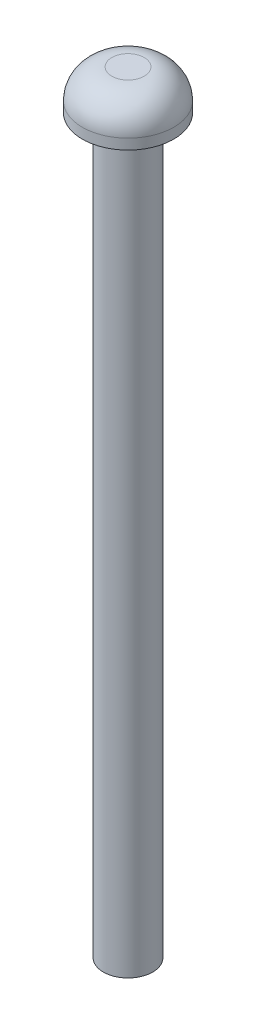
SolidWorks part; units mm, degrees
ref_plane "Alzado" through (0, 0, 0) normal (0, 0, 1) x (1, 0, 0)
ref_plane "Planta" through (0, 0, 0) normal (0, 1, 0) x (1, 0, 0)
ref_plane "Vista lateral" through (0, 0, 0) normal (1, 0, 0) x (0, 0, -1)
sketch "Croquis1" plane through (0, 0, 0) normal (0, 1, 0) x (1, 0, 0)
  circle A0 centre (0, 0) radius 1.675
  dimension "D1" = 3.35
extrude "Saliente-Extruir1" add sketch "Croquis1" against normal blind 49.65
sketch "Croquis2" plane through (0, 0, 0) normal (0, 1, 0) x (1, 0, 0)
  circle A0 centre (0, 0) radius 3.1
  dimension "D1" = 6.2
extrude "Saliente-Extruir2" add sketch "Croquis2" along normal blind 2.7
fillet "Redondeo1" radius 2 1 edges at (0, 2.7, 3.1)
